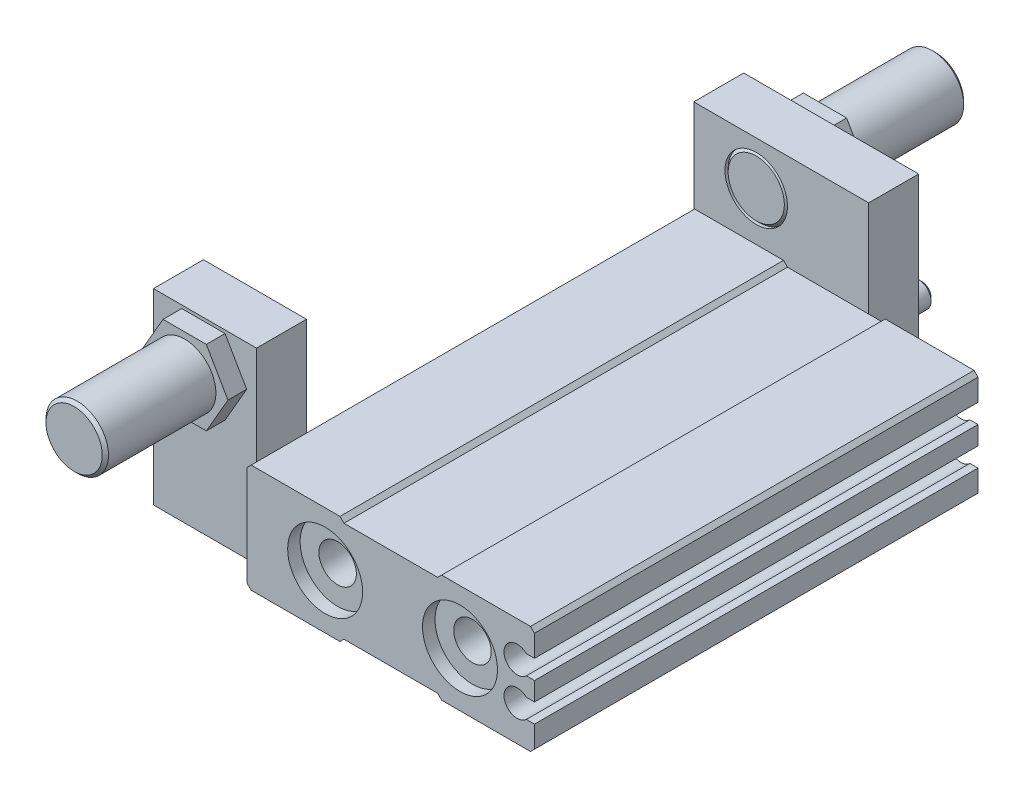
SolidWorks part; units mm, degrees
ref_plane "Front" through (0, 0, 0) normal (0, 0, 1) x (1, 0, 0)
ref_plane "Top" through (0, 0, 0) normal (0, 1, 0) x (1, 0, 0)
ref_plane "Right" through (0, 0, 0) normal (1, 0, 0) x (0, 0, -1)
ref_plane "Plane4" through (0, 0, 0) normal (0, 0, 1) x (-1, 0, 0)
sketch "Sketch1" plane through (0, 0, 53.15) normal (0, 0, 1) x (-1, 0, 0)
  line L0 (22.365, 8.6741) -> (23, 8.0391)
  line L1 (-7.5, 8.0391) -> (7.5, 8.0391)
  line L2 (22.365, 8.6741) -> (8.135, 8.6741)
  line L3 (-8.135, 8.6741) -> (-22.365, 8.6741)
  line L4 (7.5, 8.0391) -> (8.135, 8.6741)
  line L5 (-7.5, 8.0391) -> (-8.135, 8.6741)
  line L6 (-23, 8.0391) -> (-23, 4.5593)
  line L7 (-23, -8.0391) -> (-22.365, -8.6741)
  line L8 (-7.5, -8.0391) -> (-8.135, -8.6741)
  line L9 (-23, 1.4859) -> (-23, -1.4859)
  line L10 (-23, -4.5593) -> (-23, -8.0391)
  line L11 (-23, 8.0391) -> (-22.365, 8.6741)
  line L12 (23, 8.0391) -> (23, -8.0391)
  line L14 (-50, 0) -> (50, 0) construction
  line L15 (-8.135, -8.6741) -> (-22.365, -8.6741)
  line L16 (-21.7027, -4.5593) -> (-23, -4.5593)
  line L18 (-7.5, -8.0391) -> (7.5, -8.0391)
  line L19 (7.5, -8.0391) -> (8.135, -8.6741)
  line L20 (23, -8.0391) -> (22.365, -8.6741)
  line L22 (-23, 0) -> (23, 0) construction
  line L23 (0, 0) -> (0, 8.0391) construction
  line L26 (22.365, -8.6741) -> (8.135, -8.6741)
  line L27 (-21.7027, -1.4859) -> (-23, -1.4859)
  line L28 (-21.7027, 1.4859) -> (-23, 1.4859)
  line L29 (-21.7027, 4.5593) -> (-23, 4.5593)
  arc A0 (-21.7027, 1.4859) -> (-21.7027, 4.5593) centre (-20.2409, 3.0226) ccw
  arc A1 (-21.7027, -4.5593) -> (-21.7027, -1.4859) centre (-20.2409, -3.0226) ccw
  circle A2 centre (-11.0744, 0) radius 9.652 construction
  dimension "D5" = 4.2418
  dimension "D9" = 9.652
  dimension "D1" = 17.3482
  dimension "D2" = 45
  dimension "D3" = 0.635
  dimension "D4" = 3.0226
  dimension "D6" = 15
  dimension "D7" = 11.0744
  dimension "D8" = 3.0734
  dimension "D10" = 8.6741
extrude "Base-Extrude" add sketch "Sketch1" along normal up to surface (71 mm away)
ref_plane "Plane8" through (0, 0, 51.15) normal (0, 0, 1) x (1, 0, 0)
sketch "Sketch2" plane through (0, 0, 53.15) normal (0, 0, -1) x (-1, 0, 0)
  line L0 (34.65, 0) -> (-34.65, 0) construction
  line L5 (0, 8.0391) -> (0, -8.0391) construction
  line L6 (7.5, 8.0391) -> (-7.5, 8.0391) construction
  line L7 (-7.5, -8.0391) -> (7.5, -8.0391) construction
  circle A0 centre (-11.0744, 0) radius 6
  circle A1 centre (10.5156, 0) radius 6
  dimension "D1" = 12
  dimension "D3" = 11.0744
  dimension "D2" = 21.59
extrude "Cut-Extrude1" cut sketch "Sketch2" along normal up to surface (69.7 mm away)
sketch "Sketch4" plane through (0, 0, 51.15) normal (0, 0, 1) x (1, 0, 0)
  circle A2 centre (11.0744, 0) radius 6 construction
  circle A3 centre (-10.5156, 0) radius 6 construction
  circle A4 centre (11.0744, 0) radius 6
  circle A5 centre (-10.5156, 0) radius 6
extrude "Boss-Extrude1" add sketch "Sketch4" against normal blind 10
sketch "Sketch19" plane through (0, 0, 51.15) normal (0, 0, 1) x (1, 0, 0)
  circle A0 centre (11.0744, 0) radius 3
  circle A1 centre (-10.5156, 0) radius 3
  circle A2 centre (-10.5156, 0) radius 6 construction
  circle A3 centre (11.0744, 0) radius 6 construction
  dimension "D1" = 6
extrude "Cut-Extrude3" cut sketch "Sketch19" against normal up to next
hole_wizard "#10-32 Tapped Hole1" positions "Sketch21" profile "Sketch20" tap size "#10-32" standard "Ansi Inch"
sketch "Sketch21" plane through (0, -8.0391, 0) normal (0, -1, 0) x (1, 0, 0)
  point P0 (0, 30.15)
  point P1 (0, 0.15)
sketch "Sketch20" plane through (0, -8.0391, 30.15) normal (1, 0, 0) x (0, 0, -1)
  line L0 (0, 0) -> (0, 14.8277)
  line L1 (0, 14.8277) -> (2.0193, 13.6144)
  line L2 (2.0193, 13.6144) -> (2.0193, 9.652)
  line L3 (2.0193, 9.652) -> (2.413, 9.652)
  line L4 (2.413, 9.652) -> (2.413, 0)
  line L5 (2.413, 0) -> (0, 0)
  line L10 (0, 14.8277) -> (-2.0193, 13.6144) construction
  line L11 (0, -6.35) -> (0, 107.95) construction
  dimension "Tap Drill Dia." = 4.0386
  dimension "Tap Drill Depth" = 13.6144
  dimension "Thread Dia." = 4.826
  dimension "Thread Depth" = 9.652
  dimension "Drill Angle" = 118
hole_wizard "#4-40 Tapped Hole1" positions "Sketch23" profile "Sketch22" tap size "#4-40" standard "Ansi Inch"
sketch "Sketch23" plane through (0, 0, -17.85) normal (0, 0, -1) x (-1, 0, 0)
  line L0 (8.135, -8.6741) -> (22.365, -8.6741) construction
  point P0 (20, -4.6741)
  point P1 (20, 4.3259)
  point P2 (-3, -4.6741)
  point P3 (-3, 4.3259)
  dimension "D1" = 4
  dimension "D2" = 9
  dimension "D3" = 23
  dimension "D4" = 20
sketch "Sketch22" plane through (-20, -4.6741, -17.85) normal (1, 0, 0) x (0, 1, 0)
  line L0 (0, 0) -> (0, 9.5438)
  line L1 (0, 9.5438) -> (1.1303, 8.8646)
  line L2 (1.1303, 8.8646) -> (1.1303, 5.6896)
  line L3 (1.1303, 5.6896) -> (1.4224, 5.6896)
  line L4 (1.4224, 5.6896) -> (1.4224, 0)
  line L5 (1.4224, 0) -> (0, 0)
  line L10 (0, 9.5438) -> (-1.1303, 8.8646) construction
  line L11 (0, -6.35) -> (0, 107.95) construction
  dimension "Tap Drill Dia." = 2.2606
  dimension "Tap Drill Depth" = 8.8646
  dimension "Thread Dia." = 2.8448
  dimension "Thread Depth" = 5.6896
  dimension "Drill Angle" = 118
hole_wizard "Hole1" positions "Sketch25" profile "Sketch24" legacy
sketch "Sketch25" plane through (0, -8.6741, 0) normal (0, -1, 0) x (1, 0, 0)
  point P0 (-19, 39.65)
sketch "Sketch24" plane through (-19, -8.6741, 39.65) normal (1, 0, 0) x (0, 0, -1)
  line L0 (0, 0) -> (0, 3.5)
  line L1 (0, 3.5) -> (2, 3.5)
  line L2 (2, 3.5) -> (2, 0)
  line L3 (2, 0) -> (0, 0)
  line L4 (0, 110) -> (0, -10) construction
  dimension "Diameter" = 4
  dimension "Depth" = 3.5
sketch "Sketch27" plane through (0, -8.6741, 0) normal (0, -1, 0) x (1, 0, 0)
  line L0 (-23, 4.65) -> (-19, 4.65) construction
  line L1 (-23, 53.15) -> (-23, -17.85) construction
  line L2 (-23, 7.15) -> (-19, 7.15) construction
  line L3 (-23, 2.15) -> (-19, 2.15) construction
  line L4 (-21, 5.15) -> (-21, 4.15)
  line L5 (-17, 5.15) -> (-17, 4.15)
  arc A0 (-21, 4.15) -> (-17, 4.15) centre (-19, 4.15) ccw
  arc A1 (-17, 5.15) -> (-21, 5.15) centre (-19, 5.15) ccw
  dimension "D1" = 4
  dimension "D2" = 5
extrude "Cut-Extrude4" cut sketch "Sketch27" against normal blind 3.5
hole_wizard "#10-32 Tapped Hole2" positions "Sketch29" profile "Sketch28" tap size "#10-32" standard "Ansi Inch"
sketch "Sketch29" plane through (-23, 0, 0) normal (-1, 0, 0) x (0, 0, 1)
  line L0 (53.15, 8.0391) -> (53.15, -8.0391) construction
  line L1 (-17.85, -8.0391) -> (-17.85, 8.0391) construction
  line L2 (-17.85, -8.6741) -> (53.15, -8.6741) construction
  point P0 (34.55, -0.1741)
  point P1 (-14.05, -0.1741)
  dimension "D1" = 18.6
  dimension "D2" = 3.8
  dimension "D3" = 8.5
sketch "Sketch28" plane through (-23, -0.1741, 34.55) normal (0, 1, 0) x (0, 0, 1)
  line L0 (0, 0) -> (0, 14.8277)
  line L1 (0, 14.8277) -> (2.0193, 13.6144)
  line L2 (2.0193, 13.6144) -> (2.0193, 9.652)
  line L3 (2.0193, 9.652) -> (2.413, 9.652)
  line L4 (2.413, 9.652) -> (2.413, 0)
  line L5 (2.413, 0) -> (0, 0)
  line L10 (0, 14.8277) -> (-2.0193, 13.6144) construction
  line L11 (0, -6.35) -> (0, 107.95) construction
  dimension "Tap Drill Dia." = 4.0386
  dimension "Tap Drill Depth" = 13.6144
  dimension "Thread Dia." = 4.826
  dimension "Thread Depth" = 9.652
  dimension "Drill Angle" = 118
sketch "Sketch30" plane through (0, 0, -17.85) normal (0, 0, -1) x (-1, 0, 0)
  line L0 (-7.5, -8.0391) -> (7.5, -8.0391) construction
  line L1 (-5.5, 23.4609) -> (22.5, 23.4609)
  line L2 (-5.5, 23.4609) -> (-5.5, -7.5391)
  line L3 (-5.5, -7.5391) -> (22.5, -7.5391)
  line L4 (22.5, 23.4609) -> (22.5, -7.5391)
  line L5 (23, -8.0391) -> (23, 8.0391) construction
  dimension "D1" = 0.5
  dimension "D2" = 0.5
  dimension "D3" = 31
  dimension "D4" = 28
extrude "Boss-Extrude2" add sketch "Sketch30" along normal blind 8
sketch "Sketch31" plane through (0, 0, -25.85) normal (0, 0, -1) x (-1, 0, 0)
  line L0 (19.4282, 16.4609) -> (15.9641, 22.4609)
  line L1 (15.9641, 22.4609) -> (9.0359, 22.4609)
  line L2 (9.0359, 22.4609) -> (5.5718, 16.4609)
  line L3 (5.5718, 16.4609) -> (9.0359, 10.4609)
  line L4 (9.0359, 10.4609) -> (15.9641, 10.4609)
  line L5 (15.9641, 10.4609) -> (19.4282, 16.4609)
  line L6 (22.5, 23.4609) -> (-5.5, 23.4609) construction
  line L7 (22.5, -7.5391) -> (22.5, 23.4609) construction
  circle A0 centre (12.5, 16.4609) radius 6.9282 construction
  dimension "D1" = 7
  dimension "D2" = 10
  dimension "D3" = 12
extrude "Boss-Extrude3" add sketch "Sketch31" along normal blind 3
sketch "Sketch35" plane through (0, 0, -25.85) normal (0, 0, -1) x (-1, 0, 0)
  circle A0 centre (20, 4.3259) radius 2
  circle A1 centre (-3, 4.3259) radius 2
  circle A2 centre (-3, -4.6741) radius 2
  circle A3 centre (20, -4.6741) radius 2
  circle A4 centre (20, -4.6741) radius 1.4224 construction
  circle A7 centre (-3, 4.3259) radius 1.4224 construction
  circle A8 centre (-3, -4.6741) radius 1.4224 construction
  circle A9 centre (20, 4.3259) radius 1.4224 construction
  dimension "D1" = 4
extrude "Boss-Extrude5" add sketch "Sketch35" along normal blind 3
chamfer "Chamfer2" distance 0.5 angle 45 4 edges at (-22, 4.3259, -28.85) (-22, -4.6741, -28.85) (1, -4.6741, -28.85) (1, 4.3259, -28.85)
ref_plane "Plane9" through (0, 0, 43.15) normal (0, 0, 1) x (1, 0, 0)
sketch "Sketch36" plane through (0, 0, 43.15) normal (0, 0, 1) x (1, 0, 0)
  line L0 (-23.5, 23.3259) -> (-23.5, 6.6741)
  line L1 (-40, 23.3259) -> (-23.5, 23.3259)
  line L2 (-40, 23.3259) -> (-40, -6.6741)
  line L3 (-40, -6.6741) -> (-23, -6.6741)
  line L4 (-23, 6.6741) -> (-23, -6.6741)
  line L5 (-23.5, 6.6741) -> (-23, 6.6741)
  line L7 (-23, 22.3259) -> (-23, -6.1741) construction
  line L8 (-22.365, -8.6741) -> (-8.135, -8.6741) construction
  line L11 (-21.0012, 8.6741) -> (-23, 8.6741) construction
  dimension "D1" = 17
  dimension "D2" = 0.5
  dimension "D3" = 30
  dimension "D4" = 2
  dimension "D5" = 2
extrude "Boss-Extrude6" add sketch "Sketch36" along normal blind 8
sketch "Sketch37" plane through (0, 0, 51.15) normal (0, 0, 1) x (1, 0, 0)
  line L0 (-40, 23.3259) -> (-40, -6.6741) construction
  line L1 (-28.5359, 22.8259) -> (-35.4641, 22.8259)
  line L2 (-35.4641, 22.8259) -> (-38.9282, 16.8259)
  line L3 (-38.9282, 16.8259) -> (-35.4641, 10.8259)
  line L4 (-35.4641, 10.8259) -> (-28.5359, 10.8259)
  line L5 (-28.5359, 10.8259) -> (-25.0718, 16.8259)
  line L8 (-25.0718, 16.8259) -> (-28.5359, 22.8259)
  line L9 (-23.5, 23.3259) -> (-40, 23.3259) construction
  circle A0 centre (-32, 16.8259) radius 6 construction
  dimension "D1" = 8
  dimension "D2" = 6.5
  dimension "D3" = 12
extrude "Boss-Extrude7" add sketch "Sketch37" along normal blind 3
sketch "Sketch38" plane through (0, 0, 54.15) normal (0, 0, 1) x (1, 0, 0)
  line L0 (-25.0718, 16.8259) -> (-28.5359, 22.8259) construction
  line L1 (-38.9282, 16.8259) -> (-35.4641, 10.8259) construction
  line L2 (-28.5359, 22.8259) -> (-35.4641, 22.8259) construction
  circle A0 centre (-32, 16.8259) radius 6 construction
  circle A1 centre (-32, 16.8259) radius 5
  dimension "D1" = 10
ref_plane "Plane11" through (0, 16.8259, 0) normal (0, 1, 0) x (-1, 0, 0)
extrude "Cut-Extrude7" cut sketch "Sketch38" against normal up to next
sketch "Sketch44" plane through (0, 16.8259, 0) normal (0, 1, 0) x (-1, 0, 0)
  line L0 (32, 54.15) -> (32, 43.15) construction
  line L1 (28.5359, 54.15) -> (35.4641, 54.15) construction
  line L2 (9.7125, 43.15) -> (-9.7125, 43.15) construction
  line L4 (32, 71.85) -> (37, 71.85)
  line L5 (32, 71.85) -> (32, 43.15)
  line L6 (32, 43.15) -> (36.5, 43.15)
  line L7 (37, 71.85) -> (37, 43.65)
  line L8 (37, 43.65) -> (36.5, 43.15)
  line L10 (37, 43.15) -> (37, 54.15) construction
  line L11 (23.5, 43.15) -> (40, 43.15) construction
  line L12 (23.5, 51.15) -> (40, 51.15) construction
  dimension "D1" = 20.7
  dimension "D2" = 45
  dimension "D3" = 0.5
revolve "Boss-Revolve1" add sketch "Sketch44" angle 360 about L0
sketch "Sketch46" plane through (0, 0, -28.85) normal (0, 0, -1) x (-1, 0, 0)
  line L0 (19.4282, 16.4609) -> (15.9641, 22.4609) construction
  line L1 (9.0359, 10.4609) -> (15.9641, 10.4609) construction
  line L2 (9.0359, 22.4609) -> (5.5718, 16.4609) construction
  circle A0 centre (12.5, 16.4609) radius 6 construction
  circle A1 centre (12.5, 16.4609) radius 5
  dimension "D1" = 10
extrude "Cut-Extrude8" cut sketch "Sketch46" against normal up to next
ref_plane "Plane12" through (0, 16.4609, 0) normal (0, 1, 0) x (-1, 0, 0)
sketch "Sketch47" plane through (0, 16.4609, 0) normal (0, 1, 0) x (-1, 0, 0)
  line L0 (22.5, -17.85) -> (-5.5, -17.85) construction
  line L2 (17.5, -28.85) -> (17.5, -17.85) construction
  line L3 (17, -17.85) -> (12.5, -17.85)
  line L4 (12.5, -17.85) -> (12.5, -46.55)
  line L5 (17.5, -46.55) -> (17.5, -18.35)
  line L6 (12.5, -17.85) -> (12.5, -46.55) construction
  line L7 (12.5, -46.55) -> (17.5, -46.55)
  line L8 (17.5, -18.35) -> (17, -17.85)
  line L9 (22.5, -25.85) -> (-5.5, -25.85) construction
  line L10 (12.5, -17.85) -> (12.5, -28.85) construction
  dimension "D1" = 45
  dimension "D2" = 0.5
  dimension "D3" = 20.7
revolve "Boss-Revolve2" add sketch "Sketch47" angle 360 about L6
chamfer "Chamfer3" distance 0.5 angle 45 2 edges at (-7.5, 16.4609, -46.55) (-27, 16.8259, 71.85)
